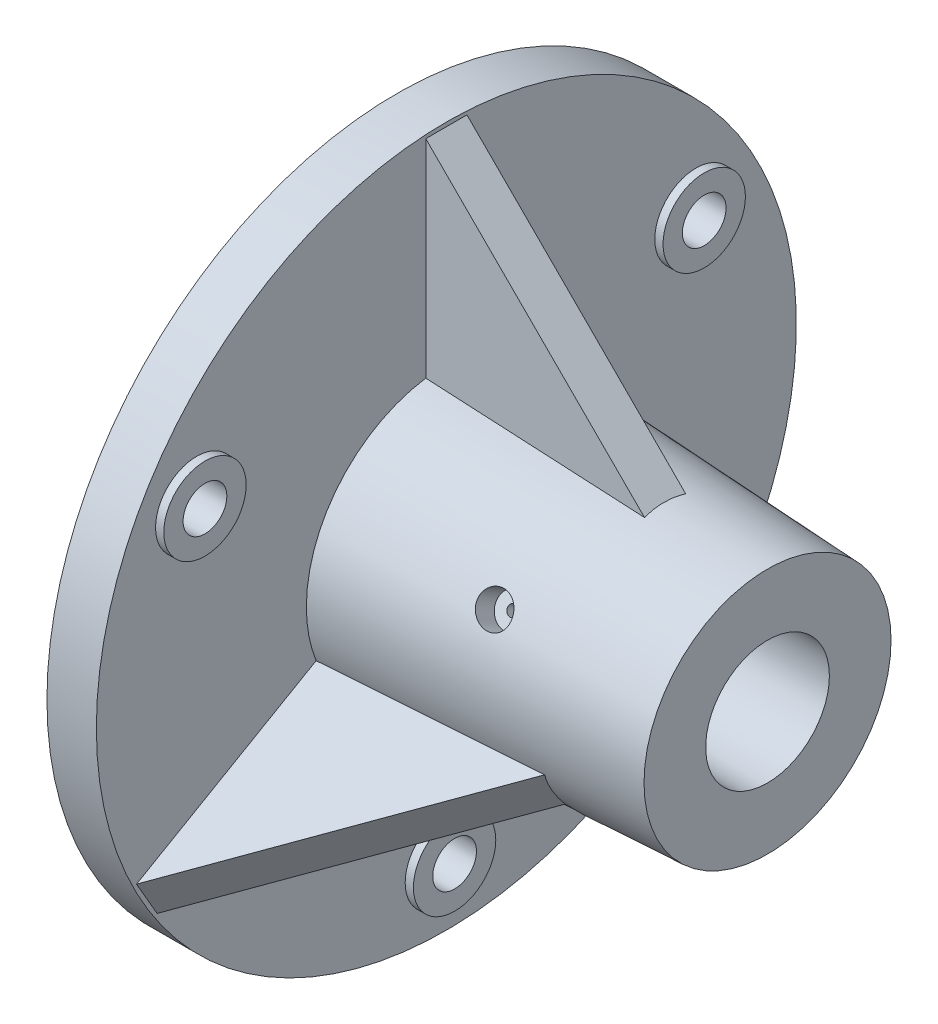
SolidWorks part; units mm, degrees
material "Gray Cast Iron"
ref_plane "Front Plane" through (0, 0, 0) normal (0, 0, 1) x (1, 0, 0)
ref_plane "Top Plane" through (0, 0, 0) normal (0, 1, 0) x (1, 0, 0)
ref_plane "Right Plane" through (0, 0, 0) normal (1, 0, 0) x (0, 0, -1)
sketch "Sketch2" plane through (0, 0, 0) normal (0, 0, 1) x (1, 0, 0)
  line L0 (-82.7617, 0) -> (196.8802, 0) construction
  line L1 (0, 107.95) -> (0, 66.675)
  line L2 (0, 107.95) -> (15.24, 107.95)
  line L3 (15.24, 107.95) -> (15.24, 43.18)
  line L4 (15.24, 43.18) -> (114.3, 38.1)
  line L5 (114.3, 38.1) -> (114.3, 0)
  line L6 (-5.08, 0) -> (114.3, 0)
  line L7 (0, 66.675) -> (-5.08, 66.675)
  line L8 (-5.08, 66.675) -> (-5.08, 0)
  dimension "D1" = 215.9
  dimension "D2" = 15.24
  dimension "D3" = 5.08
  dimension "D4" = 76.2
  dimension "D5" = 99.06
  dimension "D6" = 133.35
  dimension "D7" = 5.08
revolve "Revolve2" add sketch "Sketch2" angle 360 about L0
sketch "Sketch5" plane through (0, 0, 0) normal (0, 0, 1) x (1, 0, 0)
  line L0 (15.24, 106.68) -> (82.1724, 39.7476)
  line L1 (15.24, -107.95) -> (15.24, 107.95) construction
  line L2 (114.3, 38.1) -> (15.24, 43.18) construction
  line L3 (0, 0) -> (40.4162, 0) construction
  dimension "D1" = 45
  dimension "D2" = 1.27
rib "Rib3" sketch "Sketch5" sketch "Sketch5" thickness 12.7 extrusion direction parallel to sketch draft on no parameters "D1"=12.7
pattern_circular "CirPattern1" count 3 over 360 about axis through (0, 0, 0) along (1, 0, 0) of "Rib3"
sketch "Sketch6" plane through (15.24, 0, 0) normal (1, 0, 0) x (0, 0, -1)
  line L0 (0, 0) -> (76.9897, 44.45) construction
  line L1 (0, 0) -> (0, 88.9) construction
  line L2 (0, 0) -> (-76.9897, 44.45) construction
  line L3 (0, 0) -> (0, -88.9) construction
  circle A0 centre (0, 0) radius 88.9 construction
  circle A1 centre (76.9897, 44.45) radius 12.7
  circle A2 centre (0, -88.9) radius 12.7
  circle A3 centre (-76.9897, 44.45) radius 12.7
  point P12 (0, 0)
  dimension "D1" = 177.8
  dimension "D3" = 25.4
  dimension "D2" = 60
  dimension "D5" = 120
  dimension "D4" = 3
extrude "Boss-Extrude1" add sketch "Sketch6" along normal blind 2.54
hole_wizard "1/2 Clearance Hole1" positions "Sketch8" profile "Sketch7" hole size "1/2" standard "ANSI Inch" end condition through all
sketch "Sketch8" plane through (17.78, 0, 0) normal (1, 0, 0) x (0, 0, -1)
  point P0 (-76.9897, 44.45)
  point P3 (76.9897, 44.45)
  point P6 (0, -88.9)
sketch "Sketch7" plane through (17.78, 44.45, 76.9897) normal (0, 1, 0) x (0, 0, -1)
  line L0 (0, 0) -> (0, 22.86)
  line L1 (0, 22.86) -> (6.7462, 22.86)
  line L2 (6.7462, 22.86) -> (6.7462, 0)
  line L5 (6.7462, 0) -> (0, 0)
  line L11 (0, -6.35) -> (0, 107.95) construction
  dimension "Thru Hole Dia." = 13.4925
  dimension "Thru Hole Depth" = 22.86
ref_plane "Plane4" through (15.24, 21.59, 37.395) normal (0.0512, 0.4993, 0.8649) x (0.9987, -0.0256, -0.0444)
sketch "Sketch10" plane through (114.3, 0, 0) normal (1, 0, 0) x (0, 0, -1)
  point P0 (0, 0)
hole_wizard "1/8 NPT Tapped Hole1" positions "Sketch12" profile "Sketch13" size "1/8" standard "ANSI Inch"
sketch "Sketch12" plane through (15.24, 21.59, 37.395) normal (0.0512, 0.4993, 0.8649) x (0.9987, -0.0256, -0.0444)
  point P0 (50.0833, 0)
sketch "Sketch13" plane through (65.2576, 20.3075, 35.1736) normal (0.6448, 0.6448, -0.4105) x (0.7626, -0.5787, 0.289)
  line L0 (0, 0) -> (0, 39.0539)
  line L1 (1.5875, 38.1) -> (0, 39.0539)
  line L2 (-1.5875, 38.1) -> (0, 39.0539) construction
  line L3 (1.5875, 38.1) -> (1.5875, 6.9342)
  line L4 (1.5875, 6.9342) -> (4.9362, 6.9342)
  line L5 (4.9362, 6.9342) -> (5.1438, 0)
  line L6 (-4.9362, 6.9342) -> (-5.1438, 0) construction
  line L7 (5.1438, 0) -> (0, 0)
  line L8 (0, -6.35) -> (0, 107.95) construction
  line L11 (-1.5875, 6.9342) -> (-4.9362, 6.9342) construction
  dimension "Tap Drill Dia." = 3.175
  dimension "Tap Drill Depth" = 38.1
  dimension "Thread Dia." = 10.2876
  dimension "Thread Angle" = 3.43
  dimension "Thread Depth" = 6.9342
  dimension "Drill Angle" = 118
sketch "Sketch14" plane through (114.3, 0, 0) normal (1, 0, 0) x (0, 0, -1)
  circle A0 centre (0, 0) radius 19.0767
  dimension "D1" = 38.1533
extrude "Cut-Extrude1" cut sketch "Sketch14" against normal through all
